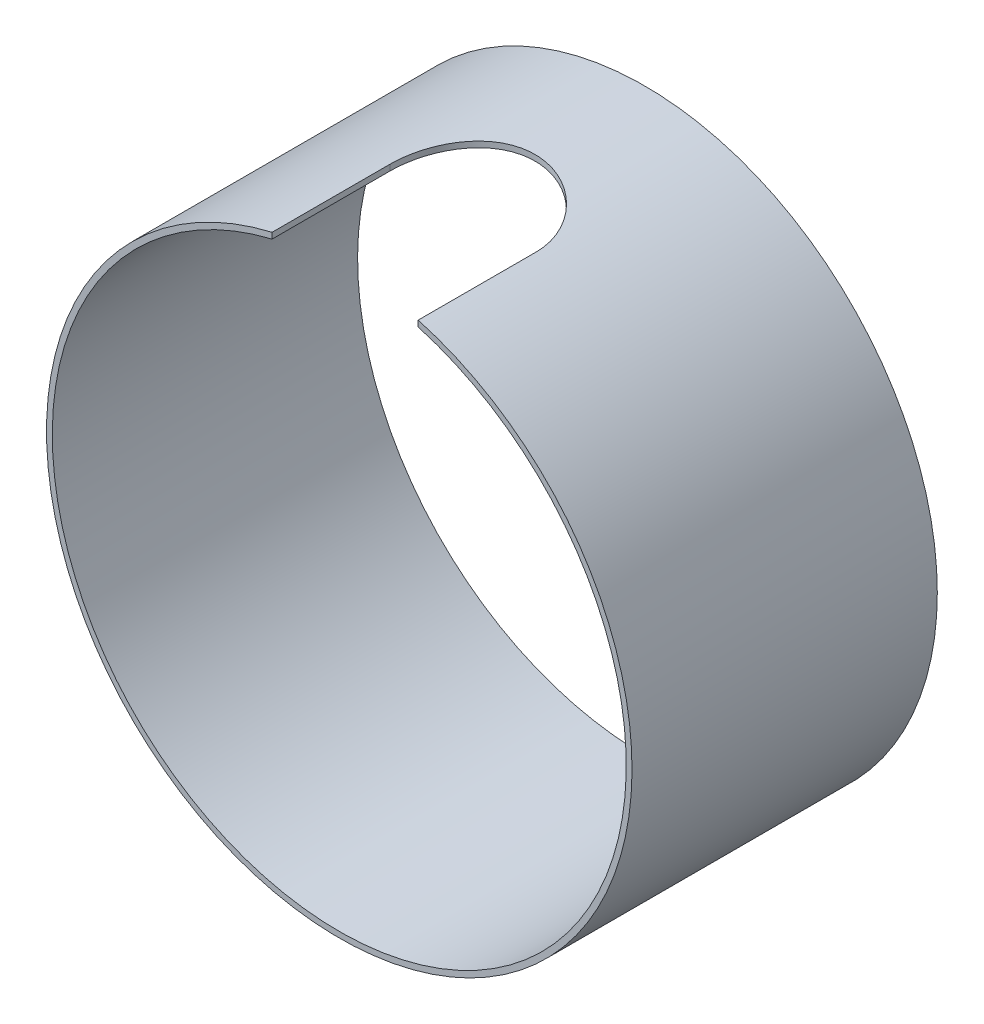
SolidWorks part; units mm, degrees
material "6061 Alloy"
ref_plane "Front Plane" through (0, 0, 0) normal (0, 0, 1) x (1, 0, 0)
ref_plane "Top Plane" through (0, 0, 0) normal (0, 1, 0) x (1, 0, 0)
ref_plane "Right Plane" through (0, 0, 0) normal (1, 0, 0) x (0, 0, -1)
sketch "Sketch1" plane through (0, 0, 0) normal (0, 0, 1) x (1, 0, 0)
  circle A0 centre (0, 0) radius 50.822
  circle A1 centre (0, 0) radius 49.822
  dimension "D2" = 1
extrude "Boss-Extrude1" add sketch "Sketch1" along normal blind 53
sketch "Sketch2" plane through (0, 0, 0) normal (0, 1, 0) x (1, 0, 0)
  line L4 (-11.666, -32.5) -> (-11.666, -53)
  line L5 (-50.822, -53) -> (50.822, -53) construction
  line L6 (-11.666, -53) -> (13.698, -53)
  line L7 (13.698, -53) -> (13.698, -32.5)
  arc A1 (13.698, -32.5) -> (-11.666, -32.5) centre (1.016, -32.5) ccw
  dimension "D1" = 20.5
extrude "Cut-Extrude1" cut sketch "Sketch2" along normal through all
